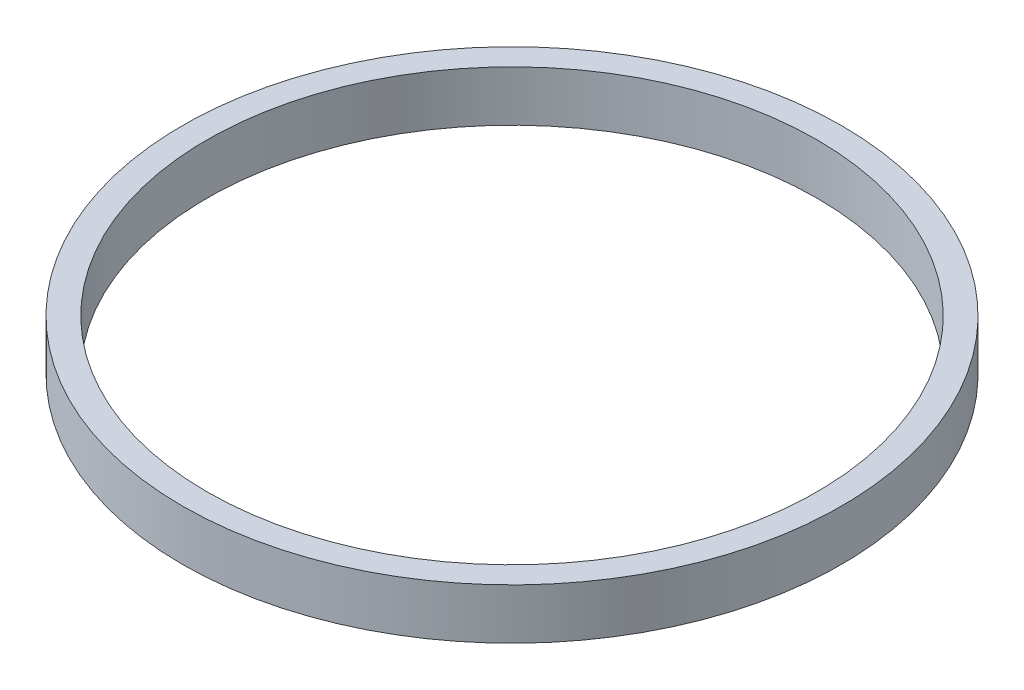
SolidWorks part; units mm, degrees
ref_plane "Alzado" through (0, 0, 0) normal (0, 0, 1) x (1, 0, 0)
ref_plane "Planta" through (0, 0, 0) normal (0, 1, 0) x (1, 0, 0)
ref_plane "Vista lateral" through (0, 0, 0) normal (1, 0, 0) x (0, 0, -1)
sketch "Croquis1" plane through (0, 0, 0) normal (0, 1, 0) x (1, 0, 0)
  circle A0 centre (0, 0) radius 30.165
  circle A1 centre (0, 0) radius 32.6
  dimension "D1" = 60.33
  dimension "D2" = 65.2
extrude "Saliente-Extruir1" add sketch "Croquis1" along normal blind 5
